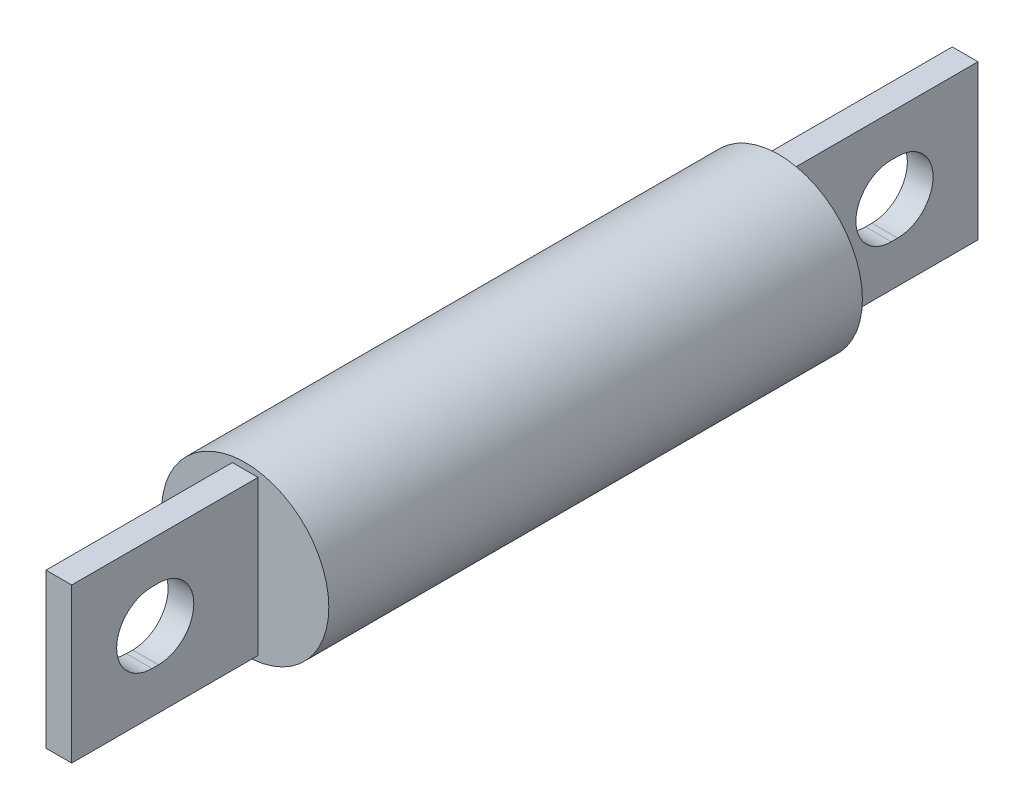
SolidWorks part; units mm, degrees
material "ABS"
ref_plane "X-Y Datum" through (0, 0, 0) normal (0, 0, 1) x (1, 0, 0)
ref_plane "X-Z Datum" through (0, 0, 0) normal (0, 1, 0) x (1, 0, 0)
ref_plane "Y-Z Datum" through (0, 0, 0) normal (1, 0, 0) x (0, 0, -1)
sketch "Sketch1" plane through (0, 0, 0) normal (0, 0, 1) x (1, 0, 0)
  circle A0 centre (0, 0) radius 10.325
  dimension "D1" = 20.65
extrude "Boss-Extrude1" add sketch "Sketch1" along normal mid plane 65.8876
sketch "Sketch2" plane through (0, 0, 0) normal (1, 0, 0) x (0, 0, -1)
  line L0 (-32.9438, 10.325) -> (-32.9438, -10.325) construction
  line L1 (-32.9438, 9.525) -> (-55.9562, 9.525)
  line L2 (-32.9438, 9.525) -> (-32.9438, -9.525)
  line L3 (-32.9438, -9.525) -> (-55.9562, -9.525)
  line L4 (-55.9562, 9.525) -> (-55.9562, -9.525)
  line L5 (-45.2501, 4.3688) -> (-46.0375, 4.3688)
  line L6 (-45.2501, -4.3688) -> (-46.0375, -4.3688)
  line L7 (0, 55) -> (0, -55) construction
  line L8 (45.2501, -4.3688) -> (46.0375, -4.3688)
  line L9 (45.2501, 4.3688) -> (46.0375, 4.3688)
  line L10 (55.9562, 9.525) -> (55.9562, -9.525)
  line L11 (32.9438, -9.525) -> (55.9562, -9.525)
  line L12 (32.9438, 9.525) -> (32.9438, -9.525)
  line L13 (32.9438, 9.525) -> (55.9562, 9.525)
  arc A0 (-46.0375, 4.3688) -> (-46.0375, -4.3688) centre (-46.0375, 0) ccw
  arc A1 (-45.2501, 4.3688) -> (-45.2501, -4.3688) centre (-45.2501, 0) cw
  arc A2 (45.2501, 4.3688) -> (45.2501, -4.3688) centre (45.2501, 0) ccw
  arc A3 (46.0375, 4.3688) -> (46.0375, -4.3688) centre (46.0375, 0) cw
  point P6 (-55.9562, 0)
  dimension "D3" = 4.3688
  dimension "D1" = 19.05
  dimension "D2" = 23.0124
  dimension "D4" = 12.3063
  dimension "D5" = 0.7874
extrude "Boss-Extrude2" add sketch "Sketch2" along normal mid plane 3.175
